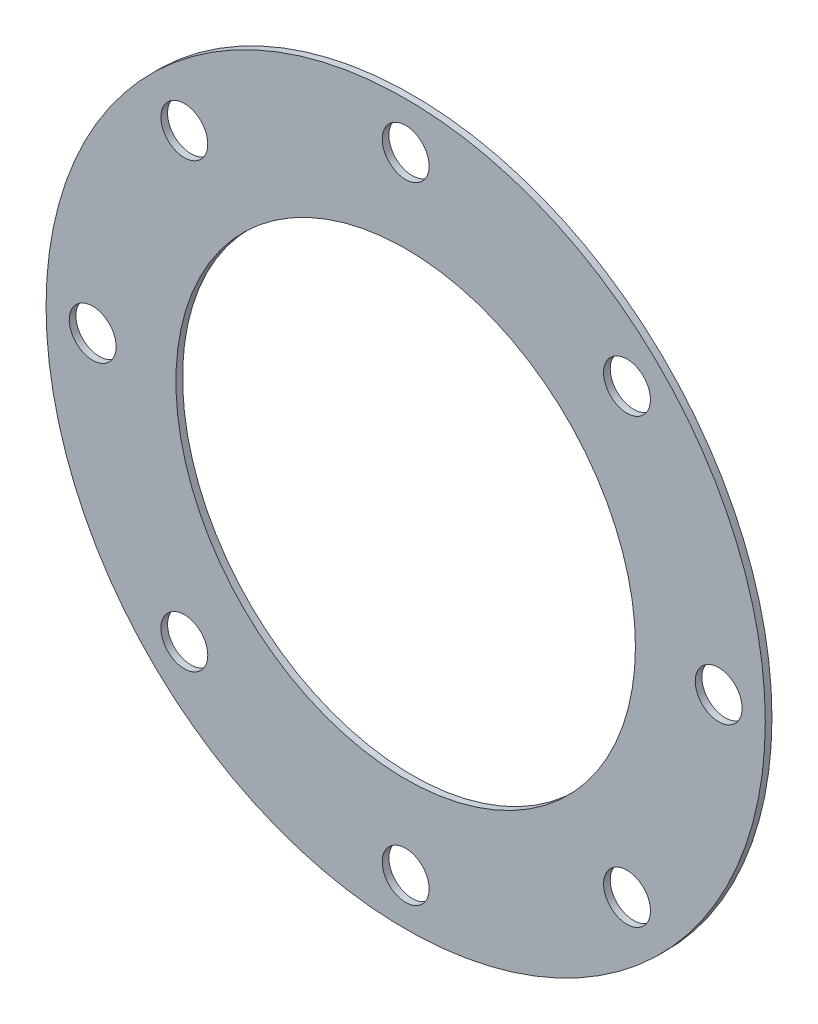
SolidWorks part; units mm, degrees
ref_plane "Front Plane" through (0, 0, 0) normal (0, 0, 1) x (1, 0, 0)
ref_plane "Top Plane" through (0, 0, 0) normal (0, 1, 0) x (1, 0, 0)
ref_plane "Right Plane" through (0, 0, 0) normal (1, 0, 0) x (0, 0, -1)
sketch "Sketch1" plane through (0, 0, 0) normal (0, 0, 1) x (1, 0, 0)
  circle A0 centre (0, 0) radius 109.5375
  circle A1 centre (0, 0) radius 171.45
  dimension "OD" = 342.9
  dimension "ID" = 219.075
extrude "Boss-Extrude1" add sketch "Sketch1" along normal mid plane 3.175
sketch "Sketch2" plane through (0, 0, 0) normal (0, 0, 1) x (1, 0, 0)
  circle A0 centre (0, 0) radius 149.225 construction
  circle A1 centre (0, 149.225) radius 11.176
  dimension "bolt circle" = 298.45
  dimension "Bolt Hole Dia" = 22.352
extrude "Cut-Extrude1" cut sketch "Sketch2" against normal through all both and the other way through all
pattern_circular "CirPattern1" count 8 over 360 about axis through (0, 0, 0) along (0, 0, 1) of "Cut-Extrude1"
